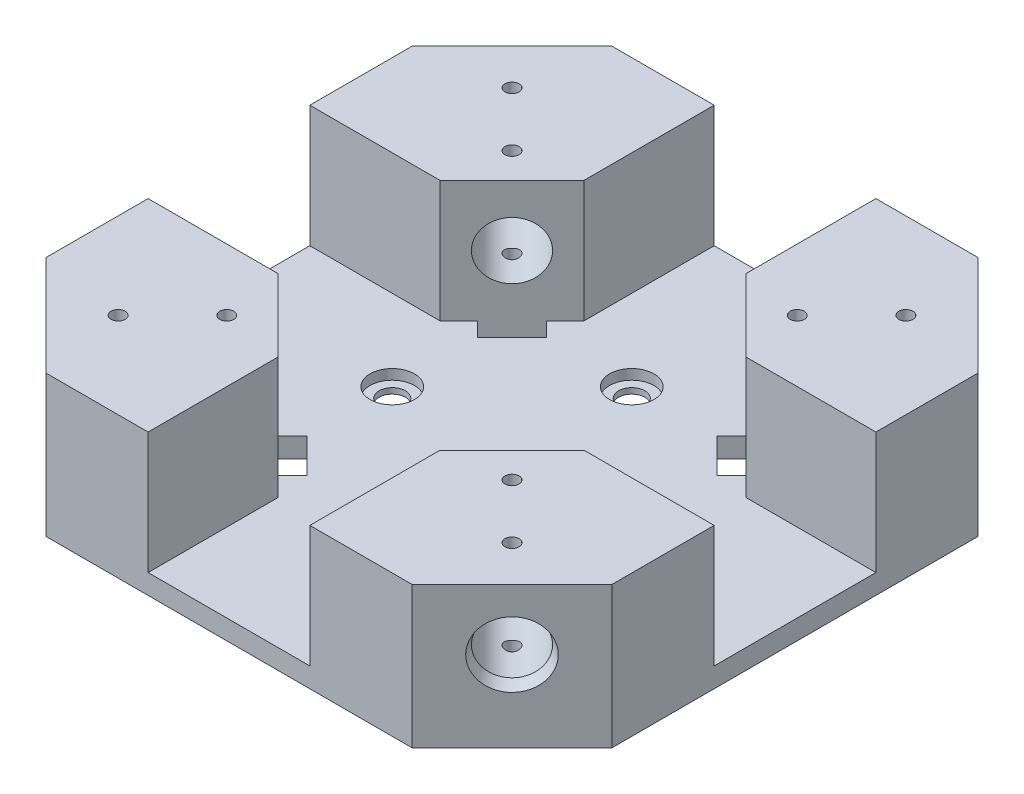
SolidWorks part; units mm, degrees
material "ABS generico"
ref_plane "Piano frontale" through (0, 0, 0) normal (0, 0, 1) x (1, 0, 0)
ref_plane "Piano superiore" through (0, 0, 0) normal (0, 1, 0) x (1, 0, 0)
ref_plane "Piano destro" through (0, 0, 0) normal (1, 0, 0) x (0, 0, -1)
sketch "Schizzo1" plane through (0, 0, 0) normal (0, 1, 0) x (1, 0, 0)
  line L0 (-28.0306, -6.8944) -> (-3.2818, -31.6431)
  line L1 (-28.0306, 108.3569) -> (111.9694, 108.3569) construction
  line L2 (-28.0306, 108.3569) -> (-28.0306, -31.6431) construction
  line L3 (-28.0306, -31.6431) -> (111.9694, -31.6431) construction
  line L4 (111.9694, 108.3569) -> (111.9694, -31.6431) construction
  line L5 (87.2207, -31.6431) -> (111.9694, -6.8944)
  line L6 (111.9694, 83.6081) -> (87.2207, 108.3569)
  line L7 (-28.0306, 83.6081) -> (-3.2818, 108.3569)
  line L8 (111.9694, 83.6081) -> (111.9694, -6.8944)
  line L9 (87.2207, -31.6431) -> (-3.2818, -31.6431)
  line L10 (-28.0306, -6.8944) -> (-28.0306, 83.6081)
  line L11 (-3.2818, 108.3569) -> (87.2207, 108.3569)
  dimension "D1" = 140
  dimension "D2" = 140
  dimension "D3" = 45
  dimension "D4" = 45
  dimension "D5" = 45
  dimension "D6" = 35
extrude "Estrusione-Estrusione2" add sketch "Schizzo1" along normal blind 35
sketch "Schizzo2" plane through (0, 35, 0) normal (0, 1, 0) x (1, 0, 0)
  line L0 (87.2207, 108.3569) -> (-3.2818, 108.3569) construction
  line L1 (21.9694, 108.3569) -> (61.9694, 108.3569)
  line L2 (21.9694, 108.3569) -> (21.9694, -31.6431)
  line L3 (21.9694, -31.6431) -> (61.9694, -31.6431)
  line L4 (61.9694, 108.3569) -> (61.9694, -31.6431)
  line L5 (-3.2818, -31.6431) -> (87.2207, -31.6431) construction
  line L7 (-28.0306, 83.6081) -> (-28.0306, -6.8944) construction
  line L8 (111.9694, -6.8944) -> (111.9694, 83.6081) construction
  line L10 (-28.0306, 58.3569) -> (111.9694, 58.3569)
  line L11 (-28.0306, 58.3569) -> (-28.0306, 18.3569)
  line L12 (-28.0306, 18.3569) -> (111.9694, 18.3569)
  line L13 (111.9694, 58.3569) -> (111.9694, 18.3569)
  line M1 (-28.0306, 83.6081) -> (-28.0306, -6.8944)
  line M3 (-3.2818, -31.6431) -> (87.2207, -31.6431)
  line M5 (111.9694, -6.8944) -> (111.9694, 83.6081)
  line M7 (87.2207, 108.3569) -> (-3.2818, 108.3569)
  dimension "D1" = 40
  dimension "D2" = 50
  dimension "D3" = 50
extrude "Taglio-Estrusione1" cut sketch "Schizzo2" against normal blind 30.1 contours L4 L12 L10 M5 | L2 L12 L4 L10 | L2 L10 L4 M7 | L12 L2 L10 M1 | L12 L2 L4 M3
sketch "Schizzo3" plane through (59.4319, 0, 59.4319) normal (0.7071, 0, 0.7071) x (0.7071, 0, -0.7071)
  line L0 (56.7993, 0) -> (56.7993, 35) construction
  line L1 (39.2993, 0) -> (74.2993, 0) construction
  line L2 (39.2993, 35) -> (74.2993, 35) construction
  line L5 (39.2993, 35) -> (39.2993, 0) construction
  line L6 (74.2993, 35) -> (74.2993, 0) construction
  line L7 (39.2993, 17.5) -> (74.2993, 17.5) construction
  line L8 (39.2993, 4.9) -> (74.2993, 4.9) construction
  circle A0 centre (56.7993, 19.95) radius 7.1
  dimension "D2" = 14.2
  dimension "D1" = 15.05
  dimension "D3" = 4.9
extrude "Taglio-Estrusione2" cut sketch "Schizzo3" against normal through all
sketch "Schizzo4" plane through (97.7888, 0, -97.7888) normal (0.7071, 0, -0.7071) x (-0.7071, 0, -0.7071)
  line L1 (-20.0545, 17.5) -> (14.9455, 17.5) construction
  line L2 (-20.0545, 35) -> (-20.0545, 0) construction
  line L3 (14.9455, 35) -> (14.9455, 0) construction
  line L4 (-2.5545, 0) -> (-2.5545, 35) construction
  line L5 (-20.0545, 0) -> (14.9455, 0) construction
  line L6 (-20.0545, 35) -> (14.9455, 35) construction
  line L7 (-20.0545, 19.95) -> (14.9455, 19.95) construction
  circle A0 centre (-2.5545, 19.95) radius 7.1
  dimension "D2" = 14.2
  dimension "D1" = 2.45
extrude "Taglio-Estrusione3" cut sketch "Schizzo4" against normal through all
sketch "Schizzo6" plane through (0, 35, 0) normal (0, 1, 0) x (1, 0, 0)
  line L0 (21.9694, 0.5378) -> (4.1504, 18.3569)
  line L1 (4.1504, 18.3569) -> (21.9694, 18.3569)
  line L2 (21.9694, 18.3569) -> (21.9694, 0.5378)
  line L3 (41.9694, 108.3569) -> (41.9694, -31.6431) construction
  line L4 (61.9694, 108.3569) -> (21.9694, 108.3569) construction
  line L5 (21.9694, -31.6431) -> (61.9694, -31.6431) construction
  line L6 (111.9694, 38.3569) -> (-28.0306, 38.3569) construction
  line L7 (111.9694, 18.3569) -> (111.9694, 58.3569) construction
  line L8 (-28.0306, 58.3569) -> (-28.0306, 18.3569) construction
  line L9 (4.1504, 58.3569) -> (21.9694, 76.176)
  line L10 (21.9694, 76.176) -> (21.9694, 58.3569)
  line L11 (21.9694, 58.3569) -> (4.1504, 58.3569)
  line L12 (61.9694, 76.176) -> (79.7885, 58.3569)
  line L13 (79.7885, 58.3569) -> (61.9694, 58.3569)
  line L14 (61.9694, 58.3569) -> (61.9694, 76.176)
  line L15 (79.7885, 18.3569) -> (61.9694, 0.5378)
  line L16 (61.9694, 0.5378) -> (61.9694, 18.3569)
  line L17 (61.9694, 18.3569) -> (79.7885, 18.3569)
  point P30 (41.9694, 38.3569)
extrude "Taglio-Estrusione4" cut sketch "Schizzo6" against normal blind 30.1
sketch "Schizzo7" plane through (0, 4.9, 0) normal (0, 1, 0) x (1, 0, 0)
  line L0 (41.9694, 108.3569) -> (41.9694, -31.6431) construction
  line L1 (8.8173, 13.69) -> (17.3025, 5.2047)
  line L2 (8.8173, 13.69) -> (12.3528, 17.2255)
  line L3 (12.3528, 17.2255) -> (20.8381, 8.7402)
  line L4 (17.3025, 5.2047) -> (20.8381, 8.7402)
  line L5 (61.9694, 108.3569) -> (21.9694, 108.3569) construction
  line L6 (21.9694, -31.6431) -> (61.9694, -31.6431) construction
  line L7 (111.9694, 38.3569) -> (-28.0306, 38.3569) construction
  line L8 (111.9694, 18.3569) -> (111.9694, 58.3569) construction
  line L9 (-28.0306, 58.3569) -> (-28.0306, 18.3569) construction
  line L10 (17.3025, 71.5091) -> (8.8173, 63.0238)
  line L11 (17.3025, 71.5091) -> (20.8381, 67.9735)
  line L12 (20.8381, 67.9735) -> (12.3528, 59.4883)
  line L13 (8.8173, 63.0238) -> (12.3528, 59.4883)
  line L14 (75.1216, 63.0238) -> (66.6363, 71.5091)
  line L15 (75.1216, 63.0238) -> (71.5861, 59.4883)
  line L16 (71.5861, 59.4883) -> (63.1008, 67.9735)
  line L17 (66.6363, 71.5091) -> (63.1008, 67.9735)
  line L18 (66.6363, 5.2047) -> (75.1216, 13.69)
  line L19 (66.6363, 5.2047) -> (63.1008, 8.7402)
  line L20 (63.1008, 8.7402) -> (71.5861, 17.2255)
  line L21 (75.1216, 13.69) -> (71.5861, 17.2255)
  point P35 (41.9694, 38.3569)
  dimension "D1" = 5
  dimension "D3" = 12
  dimension "D4" = 6.6
  dimension "D2" = 4
extrude "Taglio-Estrusione5" cut sketch "Schizzo7" against normal through all
sketch "Schizzo9" plane through (0, 35, 0) normal (0, 1, 0) x (1, 0, 0)
  line L0 (99.5951, -19.2687) -> (-15.6562, 95.9825) construction
  line L3 (87.2207, -31.6431) -> (111.9694, -6.8944) construction
  line L6 (-3.2818, 108.3569) -> (-28.0306, 83.6081) construction
  line L7 (99.5951, 95.9825) -> (-15.6562, -19.2687) construction
  line L8 (111.9694, 83.6081) -> (87.2207, 108.3569) construction
  line L9 (-28.0306, -6.8944) -> (-3.2818, -31.6431) construction
  circle A0 centre (90.678, 87.0654) radius 1.75
  circle A1 centre (77.243, 73.6304) radius 1.75
  circle A2 centre (90.678, -10.3517) radius 1.75
  circle A3 centre (77.243, 3.0834) radius 1.75
  circle A4 centre (-6.7391, -10.3517) radius 1.75
  circle A5 centre (6.6959, 3.0834) radius 1.75
  circle A6 centre (-6.7391, 87.0654) radius 1.75
  circle A7 centre (6.6959, 73.6304) radius 1.75
  circle A10 centre (6.6959, 73.6304) radius 1.75 construction
  circle A11 centre (-6.7391, 87.0654) radius 1.75 construction
  point P33 (41.9694, 38.3569)
  dimension "D1" = 3.5
  dimension "D2" = 3.5
  dimension "D3" = 4
extrude "Taglio-Estrusione6" cut sketch "Schizzo9" against normal through all
sketch "Schizzo10" plane through (0, 0, 0) normal (0, -1, 0) x (1, 0, 0)
  line L0 (41.9694, -67.9735) -> (41.9694, -8.7402) construction
  line L1 (12.3528, -38.3569) -> (71.5861, -38.3569) construction
  line L2 (111.9694, 6.8944) -> (111.9694, -83.6081) construction
  line L3 (12.3528, -59.4883) -> (12.3528, -38.3569) construction
  line L4 (12.3528, -38.3569) -> (12.3528, -17.2255) construction
  line L5 (20.8381, -8.7402) -> (41.9694, -8.7402) construction
  line L6 (41.9694, -8.7402) -> (63.1008, -8.7402) construction
  circle A0 centre (71.5861, -38.3569) radius 3.25
  circle A1 centre (12.3528, -38.3569) radius 3.25
  circle A2 centre (41.9694, -67.9735) radius 3.25
  circle A3 centre (41.9694, -8.7402) radius 3.25
  dimension "D1" = 6.5
extrude "Taglio-Estrusione7" cut sketch "Schizzo10" against normal up to next
chamfer "Smusso2" distance 2 distance2 1 4 edges at (41.9694, 0, -11.9902) (71.5861, 0, -41.6069) (41.9694, 0, -71.2235) (12.3528, 0, -41.6069)
sketch "Schizzo11" plane through (0, 4.9, 0) normal (0, 1, 0) x (1, 0, 0)
  circle A0 centre (41.9694, 8.7402) radius 5.5
  circle A1 centre (71.5861, 38.3569) radius 5.5
  circle A2 centre (12.3528, 38.3569) radius 5.5
  circle A3 centre (41.9694, 67.9735) radius 5.5
  dimension "D1" = 11
extrude "Taglio-Estrusione8" cut sketch "Schizzo11" against normal blind 2.5
chamfer "Smusso3" distance 3 distance2 1 2 edges at (-20.6766, 19.95, 14.2483) (-10.6357, 19.95, -101.003)
chamfer "Smusso4" distance 1 distance2 3 2 edges at (94.5746, 19.95, -101.003) (104.6155, 19.95, 14.2483)
